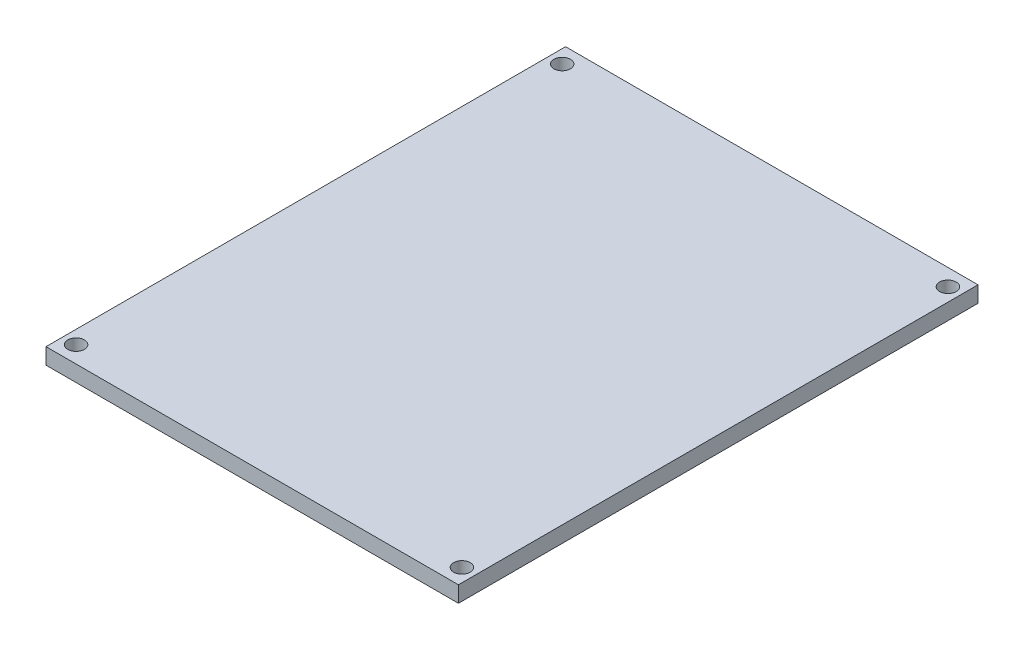
SolidWorks part; units mm, degrees
ref_plane "Front Plane" through (0, 0, 0) normal (0, 0, 1) x (1, 0, 0)
ref_plane "Top Plane" through (0, 0, 0) normal (0, 1, 0) x (1, 0, 0)
ref_plane "Right Plane" through (0, 0, 0) normal (1, 0, 0) x (0, 0, -1)
sketch "Sketch1" plane through (0, 0, 0) normal (0, 1, 0) x (1, 0, 0)
  line L0 (-9.8342, -5.6402) -> (67.1658, -5.6402)
  line L9 (67.1658, -5.6402) -> (67.1658, 91.3598)
  line L10 (-9.8342, 91.3598) -> (67.1658, 91.3598)
  line L11 (-9.8342, -5.6402) -> (-9.8342, 91.3598)
  line L12 (-9.8342, 91.3598) -> (67.1658, -5.6402) construction
  line L13 (-9.8342, -5.6402) -> (67.1658, 91.3598) construction
  circle A0 centre (-7.3473, 88.2269) radius 1.55
  circle A1 centre (64.6788, 88.2269) radius 1.55
  circle A2 centre (-7.3473, -2.5073) radius 1.55
  circle A3 centre (64.6788, -2.5073) radius 1.55
  dimension "D3" = 3.1
  dimension "D1" = 77
  dimension "D2" = 97
  dimension "D4" = 4
  dimension "D5" = 4
  dimension "D6" = 4
  dimension "D7" = 4
extrude "Boss-Extrude1" add sketch "Sketch1" along normal blind 3
